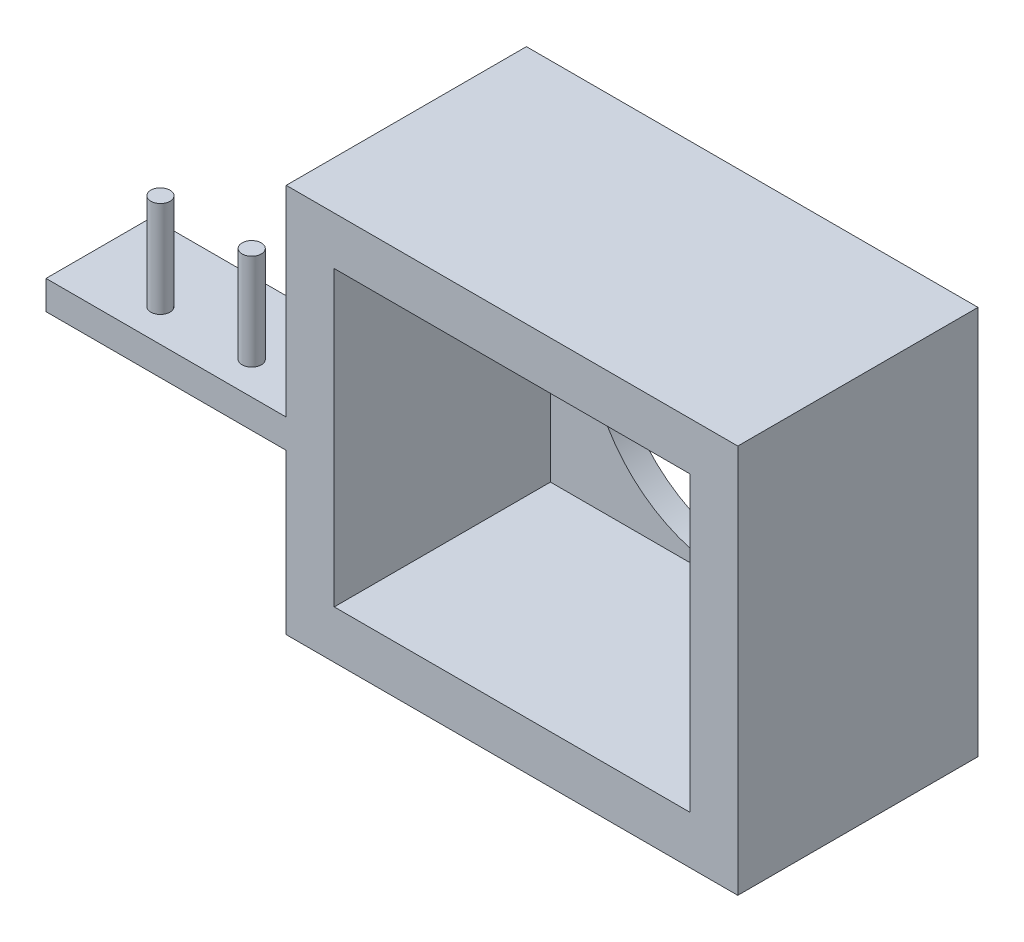
SolidWorks part; units mm, degrees
ref_plane "Alzado" through (0, 0, 0) normal (0, 0, 1) x (1, 0, 0)
ref_plane "Planta" through (0, 0, 0) normal (0, 1, 0) x (1, 0, 0)
ref_plane "Vista lateral" through (0, 0, 0) normal (1, 0, 0) x (0, 0, -1)
ref_plane "Plano1" through (0, 0, 25) normal (0, 0, 1) x (1, 0, 0)
sketch "Croquis1" plane through (0, 0, 25) normal (0, 0, 1) x (1, 0, 0)
  line L0 (-45.7431, 54.4363) -> (-45.7431, 13.9363)
  line L1 (-45.7431, 13.9363) -> (1.2569, 13.9363)
  line L2 (1.2569, 13.9363) -> (1.2569, 54.4363)
  line L3 (1.2569, 54.4363) -> (-45.7431, 54.4363)
extrude "Saliente-Extruir1" add sketch "Croquis1" against normal blind 25
sketch "Croquis2" plane through (-45.7431, 0, 0) normal (-1, 0, 0) x (0, 0, 1)
  line L0 (25, 30.5463) -> (14.0661, 30.5463)
  line L1 (14.0661, 30.5463) -> (14.0661, 33.5463)
  line L2 (14.0661, 33.5463) -> (25, 33.5463)
  line L3 (25, 33.5463) -> (25, 30.5463)
extrude "Saliente-Extruir2" add sketch "Croquis2" along normal blind 25
sketch "Croquis3" plane through (0, 0, 25) normal (0, 0, 1) x (1, 0, 0)
  line L0 (-3.7431, 49.4363) -> (-40.7431, 49.4363)
  line L1 (-40.7431, 49.4363) -> (-40.7431, 18.9363)
  line L2 (-40.7431, 18.9363) -> (-3.7431, 18.9363)
  line L3 (-3.7431, 18.9363) -> (-3.7431, 49.4363)
extrude "Cortar-Extruir1" cut sketch "Croquis3" against normal blind 22.5
ref_plane "Plano2" through (0, 0, 21.5904) normal (0, 0, 1) x (1, 0, 0)
sketch "Croquis4" plane through (0, 0, 21.5904) normal (0, 0, 1) x (1, 0, 0)
  line L0 (-51.7431, 43.5463) -> (-52.7431, 43.5463)
  line L1 (-52.7431, 43.5463) -> (-52.7431, 33.5463)
  line L2 (-52.7431, 33.5463) -> (-51.7431, 33.5463)
  line L3 (-51.7431, 33.5463) -> (-51.7431, 43.5463)
  line L4 (-52.7431, 43.5463) -> (-52.7431, 33.5463) construction
revolve "Revolución1" add sketch "Croquis4" angle 360 about L4
sketch "Croquis5" plane through (0, 0, 21.5904) normal (0, 0, 1) x (1, 0, 0)
  line L0 (-61.2431, 43.5463) -> (-62.2431, 43.5463)
  line L1 (-62.2431, 43.5463) -> (-62.2431, 33.5463)
  line L2 (-62.2431, 33.5463) -> (-61.2431, 33.5463)
  line L3 (-61.2431, 33.5463) -> (-61.2431, 43.5463)
  line L4 (-62.2431, 43.5463) -> (-62.2431, 33.5463) construction
revolve "Revolución2" add sketch "Croquis5" angle 360 about L4
hole_wizard "Taladro de margen para M251" positions "Croquis7" profile "Croquis6" hole size "M25" standard "Ansi Metric" end condition through all
sketch "Croquis7" plane through (0, 0, 2.5) normal (0, 0, 1) x (1, 0, 0)
  point P0 (-22.2431, 34.1863)
sketch "Croquis6" plane through (-22.2431, 34.1863, 2.5) normal (1, 0, 0) x (0, -1, 0)
  line L0 (0, 0) -> (0, 2.5)
  line L1 (0, 2.5) -> (14.5, 2.5)
  line L2 (14.5, 2.5) -> (14.5, 0)
  line L5 (14.5, 0) -> (0, 0)
  line L11 (0, -6.35) -> (0, 107.95) construction
  dimension "Diámetro de taladro hasta el siguiente" = 29
  dimension "Profundidad de taladro hasta el siguiente" = 2.5
